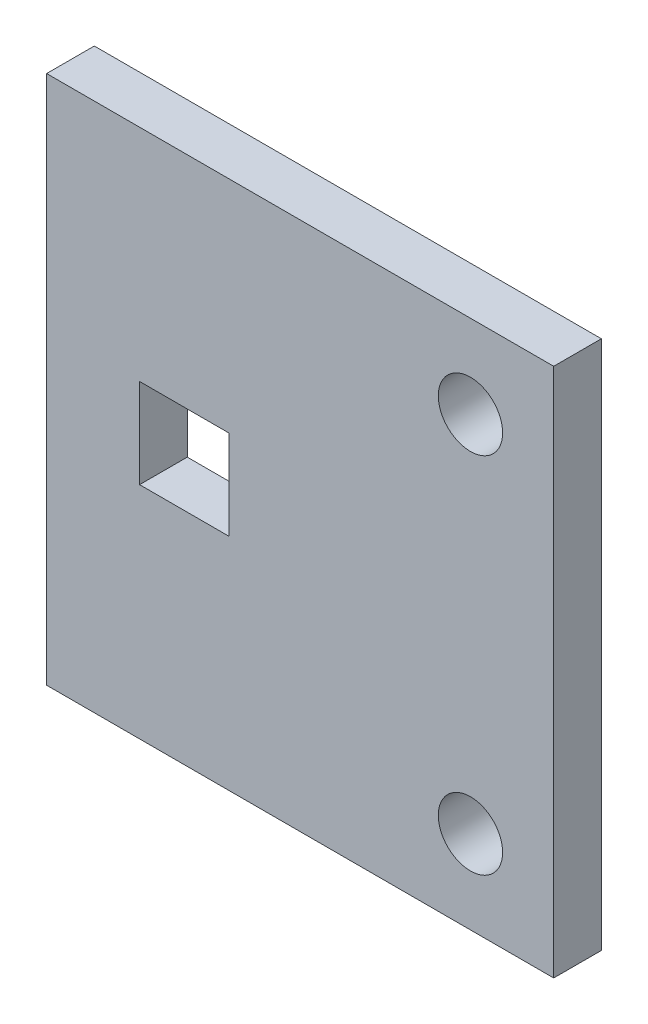
SolidWorks part; units mm, degrees
ref_plane "Front Plane" through (0, 0, 0) normal (0, 0, 1) x (1, 0, 0)
ref_plane "Top Plane" through (0, 0, 0) normal (0, 1, 0) x (1, 0, 0)
ref_plane "Right Plane" through (0, 0, 0) normal (1, 0, 0) x (0, 0, -1)
sketch "Sketch1" plane through (0, 0, 0) normal (0, 0, 1) x (1, 0, 0)
  line L0 (0, 0) -> (8.509, 0) construction
  line L1 (-8.509, -8.89) -> (8.509, -8.89)
  line L2 (-8.509, -8.89) -> (-8.509, 8.89)
  line L3 (-8.509, 8.89) -> (8.509, 8.89)
  line L4 (8.509, -8.89) -> (8.509, 8.89)
  line L5 (-8.509, -8.89) -> (8.509, 8.89) construction
  line L6 (-8.509, 8.89) -> (8.509, -8.89) construction
  line L7 (-8.509, 8.89) -> (5.715, 8.89) construction
  line L8 (-8.509, 8.89) -> (-8.509, -8.89) construction
  line L9 (-8.509, -8.89) -> (5.715, -8.89) construction
  line L10 (5.715, 8.89) -> (5.715, -8.89) construction
  line L11 (8.509, -8.89) -> (5.715, -8.89) construction
  line L12 (8.509, -8.89) -> (8.509, -6.096) construction
  line L13 (8.509, -6.096) -> (5.715, -6.096) construction
  line L14 (5.715, -8.89) -> (5.715, -6.096) construction
  line L15 (8.509, 6.096) -> (5.715, 6.096) construction
  line L17 (-8.509, 8.89) -> (-3.889, 8.89)
  line L18 (-8.509, 8.89) -> (-8.509, 0)
  line L19 (-8.509, 0) -> (-3.889, 0) construction
  line L20 (-3.889, 8.89) -> (-3.889, 0) construction
  line L21 (-2.389, 1.5) -> (-5.389, 1.5)
  line L22 (-2.389, 1.5) -> (-2.389, -1.5)
  line L23 (-2.389, -1.5) -> (-5.389, -1.5)
  line L24 (-5.389, 1.5) -> (-5.389, -1.5)
  line L25 (-2.389, 1.5) -> (-5.389, -1.5) construction
  line L26 (-2.389, -1.5) -> (-5.389, 1.5) construction
  circle A0 centre (5.715, 6.096) radius 1.0795
  circle A1 centre (5.715, -6.096) radius 1.0795
  point P0 (0, 0)
  dimension "D5" = 2.159
  dimension "D1" = 17.78
  dimension "D2" = 17.018
  dimension "D3" = 14.224
  dimension "D4" = 2.794
  dimension "D6" = 4.62
  dimension "D7" = 3
  dimension "D8" = 3
extrude "Boss-Extrude1" add sketch "Sketch1" along normal blind 1.6 contours L1 L4 L3 L2 L24 L21 L22 L23 A0 A1
equation "\"material_width\" = 0.1795"
equation "\"max32_width\" = 2.1"
equation "\"max32_length\" = 4.0"
equation "\"max32_hole_diameter\" = 0.12"
equation "\"max32_dist2hole_width\" = 0.1"
equation "\"max32_dist2hole1_length\" = 0.6"
equation "\"max32_dist2hole2_length\" = 3.8"
equation "\"head_height\" = 2.0"
equation "\"neck_height\" = \"max32_width\""
equation "\"washer_height\" = 0.1"
equation "\"wall_length\" = 3.5"
equation "\"wall_height\" = 1.5"
equation "\"extra_space\" = 0.25"
equation "\"arc_radius\" = \"wall_length\" + \"washer_height\" + \"neck_height\" + (\"head_height\"/2)"
equation "\"arc_wall_height\" = \"arc_radius\" + \"wall_length\" + \"extra_space\""
equation "\"foot_length\" = 1.0"
equation "\"peg_diameter\" = 0.2475"
equation "\"barring_diameter\" = 0.8657"
equation "\"imu_space\" = 0.8"
equation "\"encoder_height\" = 0.8587"
equation "\"encoder_sub_height\" = 0.3827"
equation "\"encoder_length\" = 1.1043"
equation "\"encoder_sub_length\" = 0.5886"
equation "\"encoder_width\" = 0.8669"
equation "\"standoff_small\" = 0.3752"
equation "\"imu_hole_diameter\" = 0.085"
equation "\"D5@Sketch1\"=\"imu_hole_diameter\""
